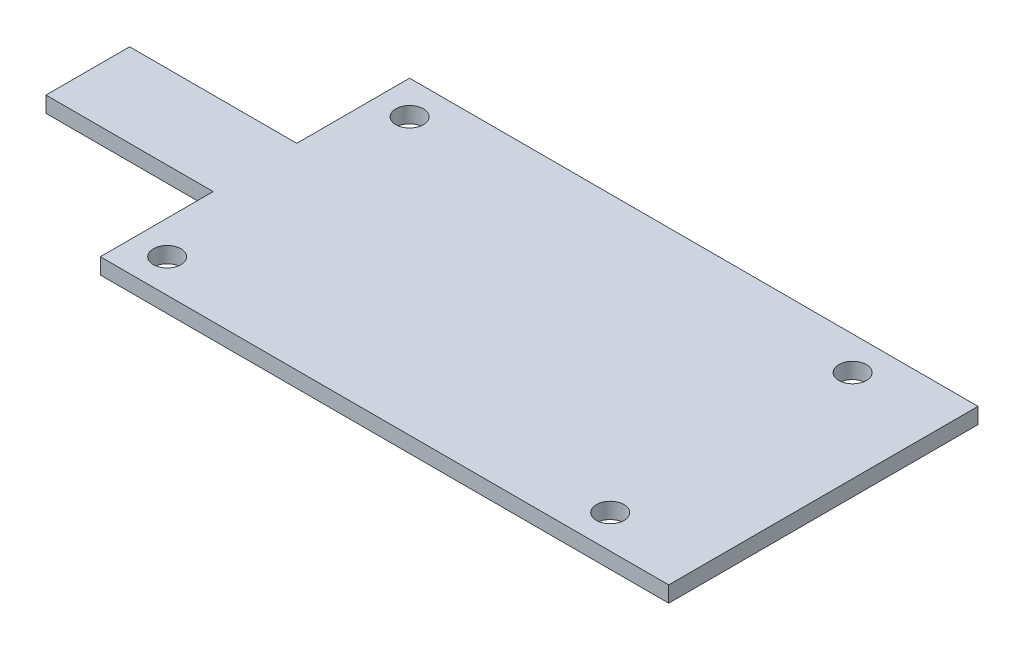
SolidWorks part; units mm, degrees
ref_plane "Front Plane" through (0, 0, 0) normal (0, 0, 1) x (1, 0, 0)
ref_plane "Top Plane" through (0, 0, 0) normal (0, 1, 0) x (1, 0, 0)
ref_plane "Right Plane" through (0, 0, 0) normal (1, 0, 0) x (0, 0, -1)
sketch "Sketch1" plane through (0, 0, 0) normal (0, 1, 0) x (1, 0, 0)
  line L0 (-59.1285, 0) -> (58.2417, 0) construction
  line L1 (-30.5, 18.5) -> (30.5, 18.5)
  line L2 (-30.5, -18.5) -> (-30.5, -5)
  line L3 (-30.5, -18.5) -> (30.5, -18.5)
  line L4 (30.5, 18.5) -> (30.5, -18.5) construction
  line L5 (0, 29.2499) -> (0, -34.5244) construction
  line L6 (-26.5, 14.5) -> (-26.5, -14.5) construction
  line L7 (-26.5, -14.5) -> (26.5, -14.5) construction
  line L8 (26.5, -14.5) -> (26.5, 14.5) construction
  line L9 (26.5, 14.5) -> (-26.5, 14.5) construction
  line L10 (30.5, 18.5) -> (37.5, 18.5)
  line L11 (37.5, 18.5) -> (37.5, -18.5)
  line L12 (37.5, -18.5) -> (30.5, -18.5)
  line L13 (-30.5, 18.5) -> (-30.5, 5)
  line L14 (-30.5, -5) -> (-50.5, -5)
  line L15 (-50.5, -5) -> (-50.5, 5)
  line L16 (-50.5, 5) -> (-30.5, 5)
  circle A0 centre (-26.5, 14.5) radius 1.65
  circle A1 centre (26.5, 14.5) radius 1.65
  circle A2 centre (26.5, -14.5) radius 1.65
  circle A3 centre (-26.5, -14.5) radius 1.65
  point P9 (30.5, 0)
  point P10 (0, 18.5)
  point P27 (-50.5, 0)
  dimension "D3" = 3.3
  dimension "D1" = 37
  dimension "D2" = 61
  dimension "D4" = 4
  dimension "D5" = 4
  dimension "D6" = 4
  dimension "D7" = 4
  dimension "D8" = 7
  dimension "D9" = 10
  dimension "D10" = 20
extrude "Boss-Extrude1" add sketch "Sketch1" along normal blind 1.9
